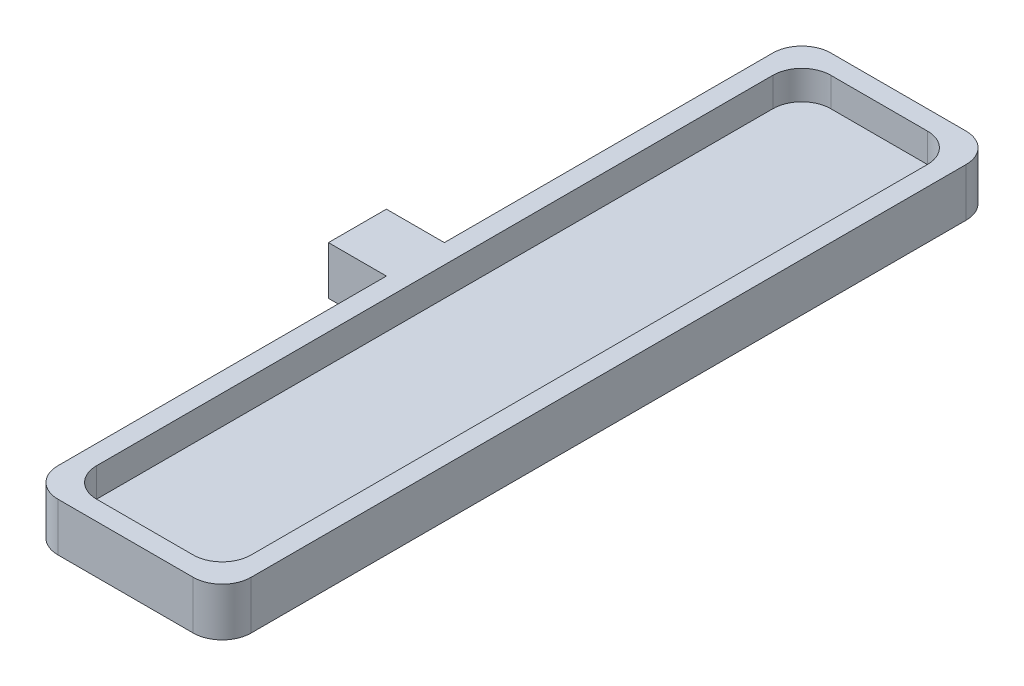
SolidWorks part; units mm, degrees
ref_plane "Front Plane" through (0, 0, 0) normal (0, 0, 1) x (1, 0, 0)
ref_plane "Top Plane" through (0, 0, 0) normal (0, 1, 0) x (1, 0, 0)
ref_plane "Right Plane" through (0, 0, 0) normal (1, 0, 0) x (0, 0, -1)
sketch "Sketch1" plane through (0, 0, 0) normal (0, 1, 0) x (1, 0, 0)
  line L1 (0, 0) -> (20, 0)
  line L2 (0, 0) -> (0, 80)
  line L3 (0, 80) -> (20, 80)
  line L4 (20, 0) -> (20, 80)
  dimension "D1" = 80
  dimension "D2" = 20
extrude "Boss-Extrude1" add sketch "Sketch1" along normal blind 5
shell "Shell1" thickness 2
fillet "Fillet1" radius 3 1 edges at (20, 2.5, 0)
fillet "Fillet2" radius 3 1 edges at (0, 2.5, 0)
fillet "Fillet3" radius 3 1 edges at (20, 2.5, -80)
fillet "Fillet4" radius 3 1 edges at (0, 2.5, -80)
fillet "Fillet5" radius 3 1 edges at (2, 3.5, -2)
fillet "Fillet6" radius 3 1 edges at (18, 3.5, -2)
fillet "Fillet7" radius 3 1 edges at (2, 3.5, -78)
fillet "Fillet8" radius 3 1 edges at (18, 3.5, -78)
sketch "Sketch2" plane through (0, 0, 0) normal (-1, 0, 0) x (0, 0, 1)
  line L0 (-40, 0) -> (-40, 5) construction
  line L1 (-77, 0) -> (-3, 0) construction
  line L2 (-77, 5) -> (-3, 5) construction
  line L4 (-43, 0) -> (-37, 0)
  line L5 (-43, 0) -> (-43, 5)
  line L6 (-43, 5) -> (-37, 5)
  line L7 (-37, 0) -> (-37, 5)
  line L8 (-43, 0) -> (-37, 5) construction
  line L9 (-43, 5) -> (-37, 0) construction
  point P6 (-40, 2.5)
  dimension "D1" = 6
extrude "Boss-Extrude2" add sketch "Sketch2" along normal blind 6
sketch "Sketch3" plane through (-6, 0, 0) normal (-1, 0, 0) x (0, 0, 1)
  line L0 (-40, 0) -> (-40, 5) construction
  line L1 (-43, 0) -> (-37, 0) construction
  line L2 (-37, 5) -> (-43, 5) construction
  circle A0 centre (-40, 2.5) radius 1.425
  point P8 (-20.4176, -17.5523)
  point P9 (-40, 2.5)
  dimension "D1" = 2.85
extrude "Cut-Extrude1" cut sketch "Sketch3" against normal blind 4 contours A0
